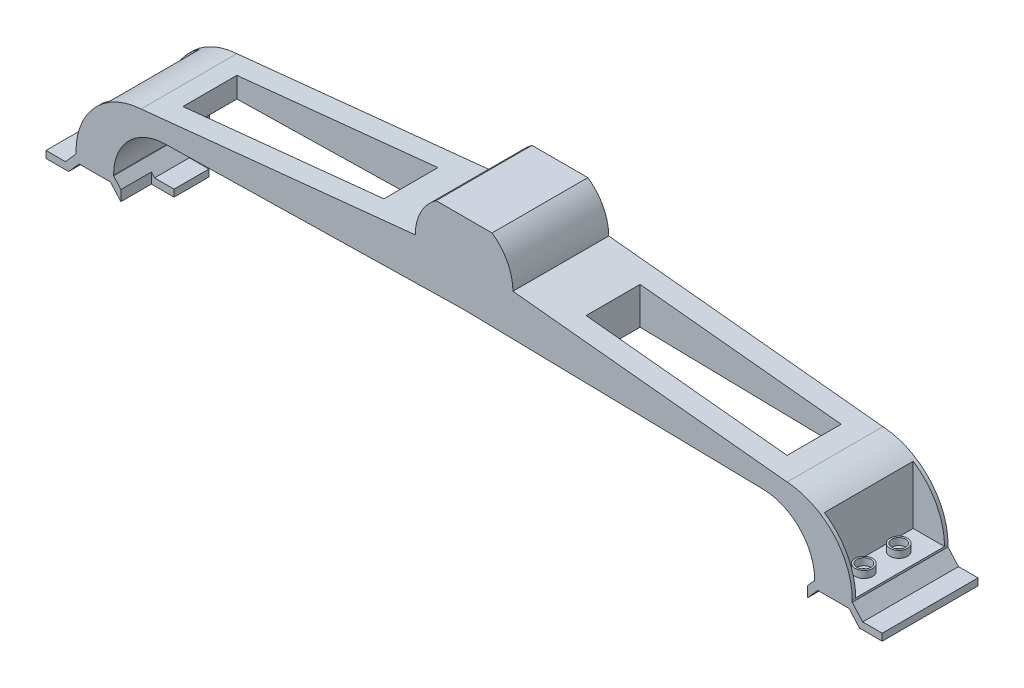
SolidWorks part; units mm, degrees
ref_plane "Front Plane" through (0, 0, 0) normal (0, 0, 1) x (1, 0, 0)
ref_plane "Top Plane" through (0, 0, 0) normal (0, 1, 0) x (1, 0, 0)
ref_plane "Right Plane" through (0, 0, 0) normal (1, 0, 0) x (0, 0, -1)
sketch "Sketch1" plane through (0, 0, 0) normal (0, 0, 1) x (1, 0, 0)
  line L0 (-4.4998, 1.4781) -> (0, 1.4781)
  line L1 (-14, -1.9177) -> (-7.5, -1.9177)
  line L2 (-7.5, -1.9177) -> (-4.4998, 1.4781)
  line L3 (0, 40.8367) -> (0, -40.8367) construction
  line L4 (-14, 0.0823) -> (-8.4017, 0.0823)
  line L5 (-8.4017, 0.0823) -> (-5.4015, 3.4781)
  line L7 (-14, 0.0823) -> (-14, -1.9177)
  line L8 (14, 0.0823) -> (14, -1.9177)
  line L10 (8.4017, 0.0823) -> (5.4015, 3.4781)
  line L11 (14, 0.0823) -> (8.4017, 0.0823)
  line L12 (7.5, -1.9177) -> (4.4998, 1.4781)
  line L13 (14, -1.9177) -> (7.5, -1.9177)
  line L14 (4.4998, 1.4781) -> (0, 1.4781)
  line L17 (5.4015, 3.4781) -> (5.4015, 3.7742)
  line L18 (-5.4015, 3.4781) -> (-5.4015, 4.0653)
  line L21 (-5.4015, 3.4781) -> (0, 3.4781) construction
  line L25 (106, 66.8163) -> (106, -34.4299) construction
  line L26 (13.2877, 24.0223) -> (91.9792, 32.0823)
  line L43 (20.1024, 18.7712) -> (106, 20.4841)
  line L44 (97.9792, 43.5823) -> (114.0208, 43.5823)
  line L45 (212, 40.8367) -> (212, -40.8367) construction
  line L46 (191.8976, 18.7712) -> (106, 20.4841)
  line L47 (198.7123, 24.0223) -> (120.0208, 32.0823)
  line L48 (217.4015, 3.4781) -> (217.4015, 4.0653)
  line L49 (206.5985, 3.4781) -> (206.5985, 3.7742)
  line L50 (207.5002, 1.4781) -> (212, 1.4781)
  line L51 (198, -1.9177) -> (204.5, -1.9177)
  line L52 (204.5, -1.9177) -> (207.5002, 1.4781)
  line L53 (198, 0.0823) -> (203.5983, 0.0823)
  line L54 (203.5983, 0.0823) -> (206.5985, 3.4781)
  line L55 (198, 0.0823) -> (198, -1.9177)
  line L56 (226, 0.0823) -> (226, -1.9177)
  line L57 (220.4017, 0.0823) -> (217.4015, 3.4781)
  line L58 (226, 0.0823) -> (220.4017, 0.0823)
  line L59 (219.5, -1.9177) -> (216.4998, 1.4781)
  line L60 (226, -1.9177) -> (219.5, -1.9177)
  line L61 (216.4998, 1.4781) -> (212, 1.4781)
  arc A0 (5.4015, 3.7742) -> (20.1024, 18.7712) centre (20.4015, 3.7742) cw
  arc A1 (13.2877, 24.0223) -> (-5.4015, 4.0653) centre (14.5985, 4.0653) ccw
  arc A2 (91.9792, 32.0823) -> (97.9792, 43.5823) centre (106, 32.0823) cw
  arc A3 (120.0208, 32.0823) -> (114.0208, 43.5823) centre (106, 32.0823) ccw
  arc A4 (198.7123, 24.0223) -> (217.4015, 4.0653) centre (197.4015, 4.0653) cw
  arc A5 (206.5985, 3.7742) -> (191.8976, 18.7712) centre (191.5985, 3.7742) ccw
  point P4 (0, 1.4781)
  point P5 (0, 1.4781)
  point P42 (106, 43.5823)
  point P43 (106, 43.5823)
  dimension "D8" = 15
  dimension "D9" = 20
  dimension "D1" = 6.5
  dimension "D2" = 4.4998
  dimension "D3" = 14
  dimension "D4" = 131.462
  dimension "D6" = 106
  dimension "D5" = 2
extrude "Boss-Extrude1" add sketch "Sketch1" along normal blind 27.5
sketch "Sketch3" plane through (0, -1.9177, 0) normal (0, -1, 0) x (1, 0, 0)
  line L0 (14, 27.5) -> (14, 0) construction
  line L1 (7.5, 27.5) -> (14, 27.5)
  line L2 (7.5, 27.5) -> (7.5, 18.75)
  line L3 (7.5, 18.75) -> (14, 18.75)
  line L4 (14, 27.5) -> (14, 18.75)
  line L5 (-33.0617, 13.75) -> (338.2826, 13.75) construction
  line L6 (106, 27.5) -> (106, 0) construction
  line L9 (-14, 27.5) -> (-7.5, 27.5) construction
  line L10 (7.5, 8.75) -> (14, 8.75)
  line L11 (14, 0) -> (14, 8.75)
  line L12 (7.5, 0) -> (14, 0)
  line L13 (7.5, 0) -> (7.5, 8.75)
  line L14 (106, 126.4644) -> (106, -81.1327) construction
  line L17 (204.5, 0) -> (204.5, 8.75)
  line L18 (204.5, 0) -> (198, 0)
  line L19 (198, 0) -> (198, 8.75)
  line L20 (204.5, 8.75) -> (198, 8.75)
  line L21 (204.5, 18.75) -> (198, 18.75)
  line L22 (198, 27.5) -> (198, 18.75)
  line L23 (204.5, 27.5) -> (198, 27.5)
  line L24 (204.5, 27.5) -> (204.5, 18.75)
  dimension "D1" = 5
  dimension "D2" = 13.75
extrude "Cut-Extrude1" cut sketch "Sketch3" against normal blind 5
sketch "Sketch5" plane through (0, 1.4781, 0) normal (0, -1, 0) x (1, 0, 0)
  line L0 (0, 37.1098) -> (0, -14.3818) construction
  line L1 (-4.4998, 27.5) -> (4.4998, 27.5) construction
  line L2 (106, 27.5) -> (106, 0) construction
  line L5 (106, 83.5918) -> (106, -78.7709) construction
  line L7 (212, 37.1098) -> (212, -14.3818) construction
  circle A0 centre (0, 18.75) radius 1
  circle A1 centre (0, 8.75) radius 1
  circle A2 centre (212, 8.75) radius 1
  circle A3 centre (212, 18.75) radius 1
  dimension "D1" = 10
  dimension "D3" = 2
  dimension "D4" = 2
  dimension "D2" = 8.75
extrude "Cut-Extrude2" cut sketch "Sketch5" against normal through all
sketch "Sketch6" plane through (-5.4015, 0, 0) normal (-1, 0, 0) x (0, 0, 1)
  line L0 (27.5, 4.0653) -> (0, 4.0653) construction
  line L1 (1, 4.0653) -> (26.5, 4.0653)
  line L2 (1, 4.0653) -> (1, 24.0653)
  line L3 (1, 24.0653) -> (26.5, 24.0653)
  line L4 (26.5, 4.0653) -> (26.5, 24.0653)
  line L5 (0, 24.0223) -> (0, 4.0653) construction
  line L6 (27.5, 4.0653) -> (27.5, 24.0223) construction
  dimension "D1" = 1
  dimension "D2" = 1
  dimension "D3" = 20
extrude "Cut-Extrude3" cut sketch "Sketch6" against normal blind 9
sketch "Sketch7" plane through (217.4015, 0, 0) normal (1, 0, 0) x (0, 0, -1)
  line L2 (-26.5, 4.0653) -> (-1, 4.0653)
  line L3 (-26.5, 4.0653) -> (-26.5, 24.0653)
  line L4 (-26.5, 24.0653) -> (-1, 24.0653)
  line L5 (-1, 4.0653) -> (-1, 24.0653)
  line L7 (-27.5, 24.0223) -> (-27.5, 4.0653) construction
  line L8 (0, 4.0653) -> (0, 24.0223) construction
  line L9 (-27.5, 4.0653) -> (0, 4.0653) construction
  dimension "D1" = 1
  dimension "D2" = 1
  dimension "D3" = 20
extrude "Cut-Extrude4" cut sketch "Sketch7" against normal blind 9
sketch "Sketch8" plane through (0, 4.0653, 0) normal (0, 1, 0) x (1, 0, 0)
  line L0 (-25.1721, -13.75) -> (330.6931, -13.75) construction
  line L1 (106, 29.7204) -> (106, -72.1298) construction
  line L2 (114.0208, 0) -> (97.9792, 0) construction
  line L3 (226, -27.5) -> (226, 0) construction
  circle A0 centre (0, -8.75) radius 2
  circle A1 centre (0, -8.75) radius 2.5
  circle A2 centre (0, -18.75) radius 2.5
  circle A3 centre (0, -18.75) radius 2
  circle A4 centre (212, -18.75) radius 2
  circle A5 centre (212, -18.75) radius 2.5
  circle A6 centre (212, -8.75) radius 2
  circle A7 centre (212, -8.75) radius 2.5
  point P19 (106, 0)
  point P22 (226, -13.75)
  dimension "D1" = 4
  dimension "D2" = 5
extrude "Boss-Extrude2" add sketch "Sketch8" along normal blind 2
sketch "Sketch10" plane through (0, 0, 0) normal (0, 1, 0) x (1, 0, 0)
  line L0 (-109.1708, -13.75) -> (373.8861, -13.75) construction
  line L2 (114.0208, 0) -> (97.9792, 0) construction
  line L3 (135.0208, -21.5) -> (192.7123, -21.5)
  line L4 (135.0208, -21.5) -> (135.0208, -6)
  line L5 (135.0208, -6) -> (192.7123, -6)
  line L6 (192.7123, -21.5) -> (192.7123, -6)
  line L7 (135.0208, -21.5) -> (192.7123, -6) construction
  line L8 (135.0208, -6) -> (192.7123, -21.5) construction
  line L10 (114.0208, -27.5) -> (114.0208, 0) construction
  line L13 (106, 21.4314) -> (106, -50.8248) construction
  line L14 (76.9792, -6) -> (19.2877, -6)
  line L15 (19.2877, -21.5) -> (19.2877, -6)
  line L16 (76.9792, -21.5) -> (19.2877, -21.5)
  line L17 (76.9792, -21.5) -> (76.9792, -6)
  line L18 (198.7123, 0) -> (120.0208, 0) construction
  line L20 (198.7123, -27.5) -> (198.7123, 0) construction
  line L21 (120.0208, -27.5) -> (120.0208, 0) construction
  point P6 (163.8666, -13.75)
  point P12 (114.0208, -13.75)
  point P25 (106, 0)
  dimension "D1" = 6
  dimension "D2" = 6
  dimension "D3" = 15
extrude "Cut-Extrude5" cut sketch "Sketch10" along normal through all
